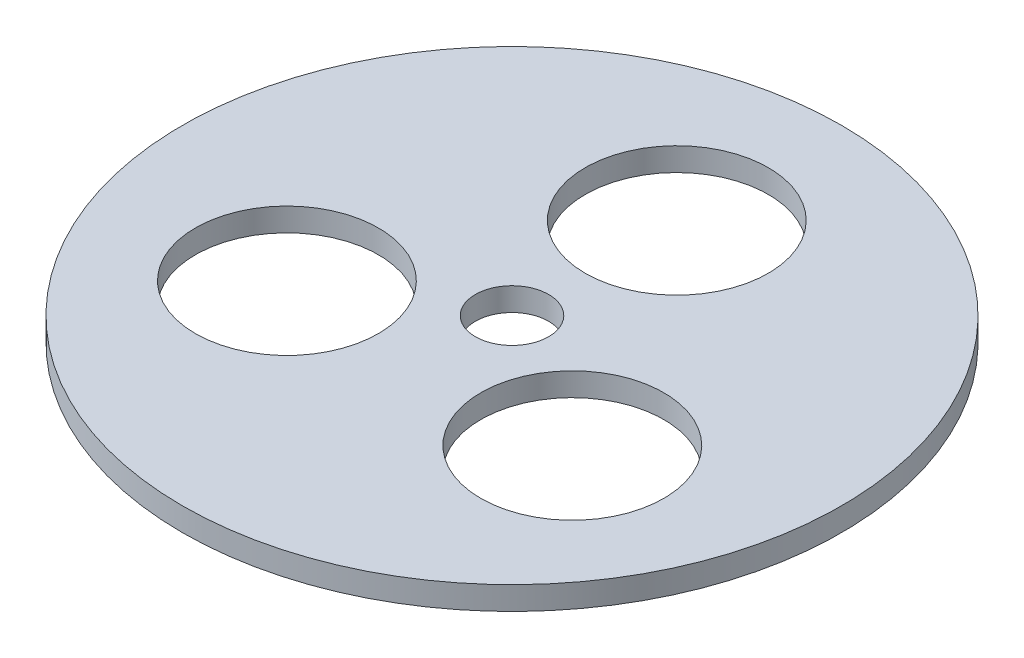
SolidWorks part; units mm, degrees
material "Acrylic (Medium-high impact)"
ref_plane "Front Plane" through (0, 0, 0) normal (0, 0, 1) x (1, 0, 0)
ref_plane "Top Plane" through (0, 0, 0) normal (0, 1, 0) x (1, 0, 0)
ref_plane "Right Plane" through (0, 0, 0) normal (1, 0, 0) x (0, 0, -1)
sketch "Sketch1" plane through (0, 0, 0) normal (0, 1, 0) x (1, 0, 0)
  line L0 (0, 0) -> (0, 45) construction
  line L1 (0, 0) -> (106.3452, -61.3984) construction
  line L2 (0, 0) -> (-119.0835, -68.7529) construction
  circle A0 centre (0, 0) radius 45
  circle A1 centre (0, 22.5) radius 12.5
  circle A2 centre (19.4856, -11.25) radius 12.5
  circle A3 centre (-19.4856, -11.25) radius 12.5
  dimension "D3" = 25
  dimension "D4" = 25
  dimension "D5" = 25
  dimension "D9" = 90
  dimension "D1" = 120
  dimension "D2" = 120
  dimension "D6" = 22.5
  dimension "D7" = 22.5
  dimension "D8" = 22.5
extrude "Boss-Extrude1" add sketch "Sketch1" along normal blind 3.175
sketch "Sketch3" plane through (0, 3.175, 0) normal (0, 1, 0) x (1, 0, 0)
  circle A0 centre (0, 0) radius 5
extrude "Cut-Extrude1" cut sketch "Sketch3" against normal blind 6.35
